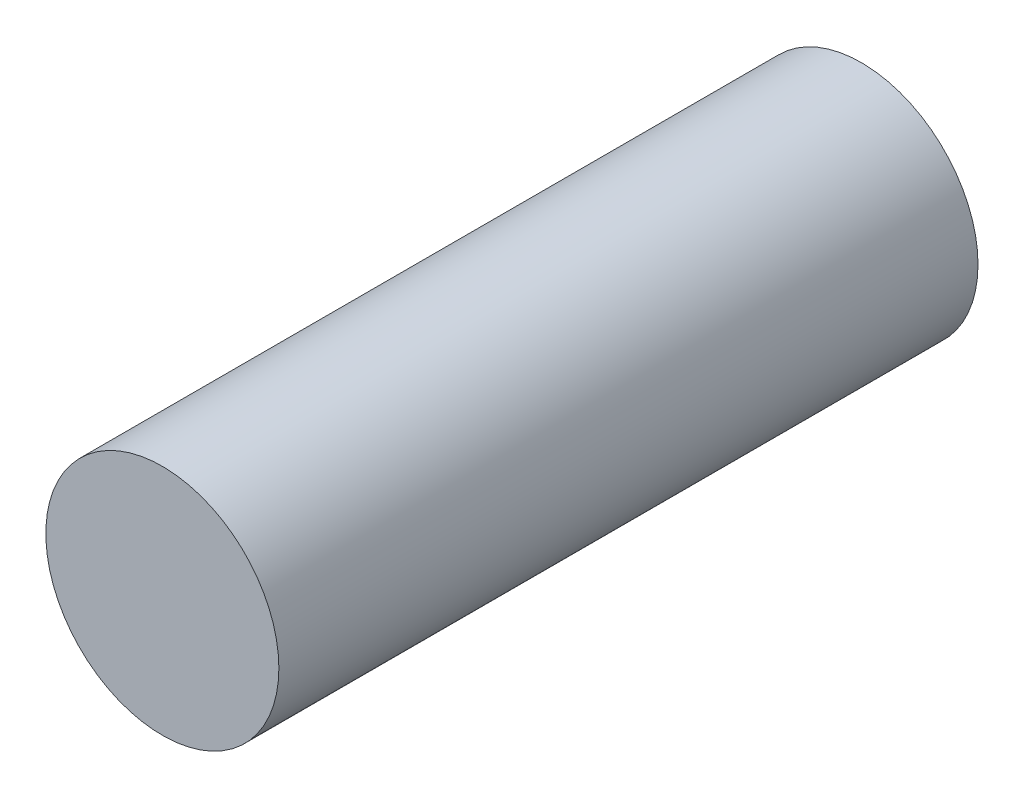
SolidWorks part; units mm, degrees
ref_plane "Front Plane" through (0, 0, 0) normal (0, 0, 1) x (1, 0, 0)
ref_plane "Top Plane" through (0, 0, 0) normal (0, 1, 0) x (1, 0, 0)
ref_plane "Right Plane" through (0, 0, 0) normal (1, 0, 0) x (0, 0, -1)
sketch "Sketch1" plane through (0, 0, 0) normal (0, 0, 1) x (1, 0, 0)
  circle A0 centre (0, 0) radius 10
  dimension "D1" = 20
extrude "Boss-Extrude1" add sketch "Sketch1" along normal blind 60
sketch "Sketch2" plane through (0, 0, 0) normal (0, 1, 0) x (1, 0, 0)
  line L0 (0, -60) -> (0, 0) construction
  line L1 (-10, -60) -> (10, -60) construction
  point P5 (0, -30)
